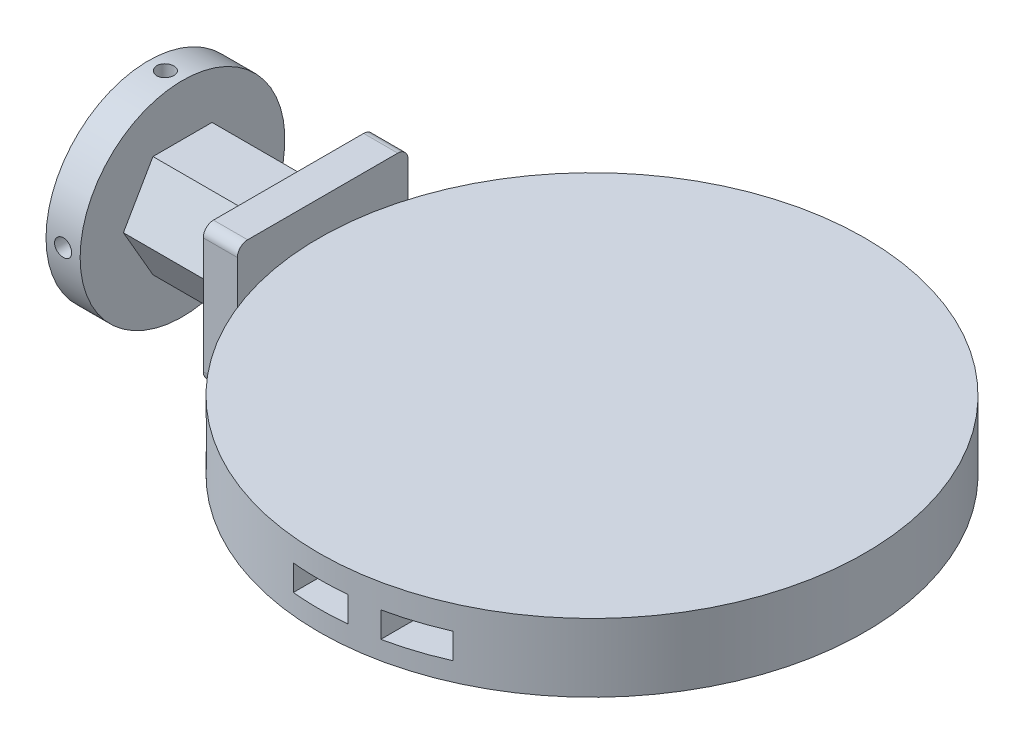
SolidWorks part; units mm, degrees
material "1060 Alloy"
ref_plane "Front Plane" through (0, 0, 0) normal (0, 0, 1) x (1, 0, 0)
ref_plane "Top Plane" through (0, 0, 0) normal (0, 1, 0) x (1, 0, 0)
ref_plane "Right Plane" through (0, 0, 0) normal (1, 0, 0) x (0, 0, -1)
sketch "Sketch2" plane through (0, 0, 0) normal (0, 1, 0) x (1, 0, 0)
  circle A0 centre (0, 0) radius 203.2
  dimension "D1" = 406.4
extrude "Boss-Extrude1" add sketch "Sketch2" along normal blind 50.8
ref_plane "Plane1" through (-228.6, 0, 0) normal (1, 0, 0) x (0, 0, -1)
ref_plane "Plane2" through (-203.2, 0, 0) normal (1, 0, 0) x (0, 0, -1)
sketch "Sketch6" plane through (-203.2, 0, 0) normal (1, 0, 0) x (0, 0, -1)
  line L0 (203.2, 50.8) -> (-203.2, 50.8) construction
  line L1 (66.253, 76.2) -> (-60.747, 76.2)
  line L2 (66.253, 76.2) -> (66.253, -25.4)
  line L3 (66.253, -25.4) -> (-60.747, -25.4)
  line L4 (-60.747, 76.2) -> (-60.747, -25.4)
  line L5 (66.253, 76.2) -> (-60.747, -25.4) construction
  line L6 (66.253, -25.4) -> (-60.747, 76.2) construction
  point P0 (2.753, 25.4)
  dimension "D1" = 127
  dimension "D2" = 101.6
  dimension "D3" = 25.4
extrude "Boss-Extrude4" add sketch "Sketch6" against normal blind 25.4 separate body
sketch "Sketch7" plane through (-228.6, 0, 0) normal (1, 0, 0) x (0, 0, -1)
  line L1 (-43.9941, 25.4) -> (-21.997, -12.7)
  line L2 (-21.997, -12.7) -> (21.997, -12.7)
  line L3 (21.997, -12.7) -> (43.9941, 25.4)
  line L4 (43.9941, 25.4) -> (21.997, 63.5)
  line L5 (21.997, 63.5) -> (-21.997, 63.5)
  line L6 (-21.997, 63.5) -> (-43.9941, 25.4)
  circle A0 centre (0, 25.4) radius 38.1 construction
  dimension "D1" = 76.2
extrude "Boss-Extrude5" add sketch "Sketch7" against normal blind 76.2
sketch "Sketch8" plane through (-304.8, 0, 0) normal (-1, 0, 0) x (0, 0, 1)
  circle A0 centre (0, 25.4) radius 76.2
  dimension "D1" = 152.4
extrude "Boss-Extrude6" add sketch "Sketch8" along normal blind 25.4
sketch "Sketch9" plane through (0, 0, 0) normal (0, 0, 1) x (1, 0, 0)
  line L0 (-304.8, 101.6) -> (-330.2, 101.6) construction
  line L1 (-304.8, -50.8) -> (-304.8, 101.6) construction
  circle A0 centre (-317.5, 25.4) radius 6.35
  dimension "D1" = 12.7
  dimension "D2" = 76.2
  dimension "D3" = 12.7
extrude "Cut-Extrude1" cut sketch "Sketch9" against normal through all and the other way through all
sketch "Sketch10" plane through (0, 0, 0) normal (0, 1, 0) x (1, 0, 0)
  line L0 (-323.85, 76.2) -> (-330.2, 76.2) construction
  line L1 (-304.8, -76.2) -> (-304.8, 76.2) construction
  circle A0 centre (-317.5, 0) radius 6.35
  dimension "D1" = 12.7
  dimension "D2" = 76.2
  dimension "D3" = 12.7
extrude "Cut-Extrude2" cut sketch "Sketch10" against normal through all and the other way through all
fillet "Fillet1" radius 7.62 1 edges at (-215.9, 76.2, -66.253)
fillet "Fillet2" radius 7.62 1 edges at (-215.9, -25.4, -66.253)
fillet "Fillet3" radius 7.62 1 edges at (-215.9, -25.4, 60.747)
fillet "Fillet4" radius 7.62 1 edges at (-215.9, 76.2, 60.747)
sketch "Sketch11" plane through (-203.2, 0, 0) normal (1, 0, 0) x (0, 0, -1)
  line L0 (149.86, 41.91) -> (-149.86, 41.91)
  line L1 (152.4, 6.35) -> (-152.4, 6.35)
  line L2 (152.4, 6.35) -> (152.4, 44.45)
  line L3 (152.4, 44.45) -> (-152.4, 44.45)
  line L4 (-152.4, 6.35) -> (-152.4, 44.45)
  line L5 (-149.86, 8.89) -> (-149.86, 41.91)
  line L6 (149.86, 8.89) -> (-149.86, 8.89)
  line L7 (149.86, 8.89) -> (149.86, 41.91)
  line L8 (130.81, 41.91) -> (130.81, 8.89)
  line L9 (128.27, 41.91) -> (128.27, 8.89)
  line L10 (109.22, 41.91) -> (109.22, 8.89)
  line L11 (106.68, 41.91) -> (106.68, 8.89)
  line L12 (87.63, 41.91) -> (87.63, 8.89)
  line L13 (85.09, 41.91) -> (85.09, 8.89)
  line L14 (-130.81, 41.91) -> (-130.81, 8.89)
  line L15 (-128.27, 41.91) -> (-128.27, 8.89)
  line L16 (-109.22, 41.91) -> (-109.22, 8.89)
  line L17 (-106.68, 41.91) -> (-106.68, 8.89)
  line L18 (-87.63, 41.91) -> (-87.63, 8.89)
  line L19 (-85.09, 41.91) -> (-85.09, 8.89)
  point P0 (0, 25.4)
  dimension "D1" = 304.8
  dimension "D2" = 38.1
  dimension "D4" = 19.05
  dimension "D5" = 2.54
  dimension "D6" = 19.05
  dimension "D7" = 2.54
  dimension "D8" = 19.05
  dimension "D9" = 2.54
  dimension "D10" = 19.05
  dimension "D11" = 2.54
  dimension "D12" = 19.05
  dimension "D13" = 2.54
  dimension "D14" = 19.05
  dimension "D15" = 2.54
  dimension "D3" = 2.54
extrude "Cut-Extrude3" cut sketch "Sketch11" along normal blind 119.38 contours L0 L8 L6 L7 | L0 L10 L6 L9 | L0 L12 L6 L11 | L16 L0 L15 L6 | L18 L0 L17 L6 | L14 L0 L5 L6
sketch "Sketch12" plane through (0, 0, 0) normal (0, 0, 1) x (1, 0, 0)
  line L1 (-20.074, 34.0023) -> (20.566, 34.0023)
  line L2 (-20.074, 34.0023) -> (-20.074, 14.9523)
  line L3 (-20.074, 14.9523) -> (20.566, 14.9523)
  line L4 (20.566, 34.0023) -> (20.566, 14.9523)
  line L5 (-20.074, 34.0023) -> (20.566, 14.9523) construction
  line L6 (-20.074, 14.9523) -> (20.566, 34.0023) construction
  line L7 (41.6556, 13.9309) -> (82.2956, 13.9309)
  line L8 (41.6556, 13.9309) -> (41.6556, 32.9809)
  line L9 (41.6556, 32.9809) -> (82.2956, 32.9809)
  line L10 (82.2956, 13.9309) -> (82.2956, 32.9809)
  line L11 (41.6556, 13.9309) -> (82.2956, 32.9809) construction
  line L12 (41.6556, 32.9809) -> (82.2956, 13.9309) construction
  point P0 (0.246, 24.4773)
  point P5 (61.9756, 23.4559)
  dimension "D1" = 19.05
  dimension "D2" = 19.05
  dimension "D3" = 40.64
  dimension "D4" = 40.64
extrude "Cut-Extrude4" cut sketch "Sketch12" against normal through all and the other way through all
